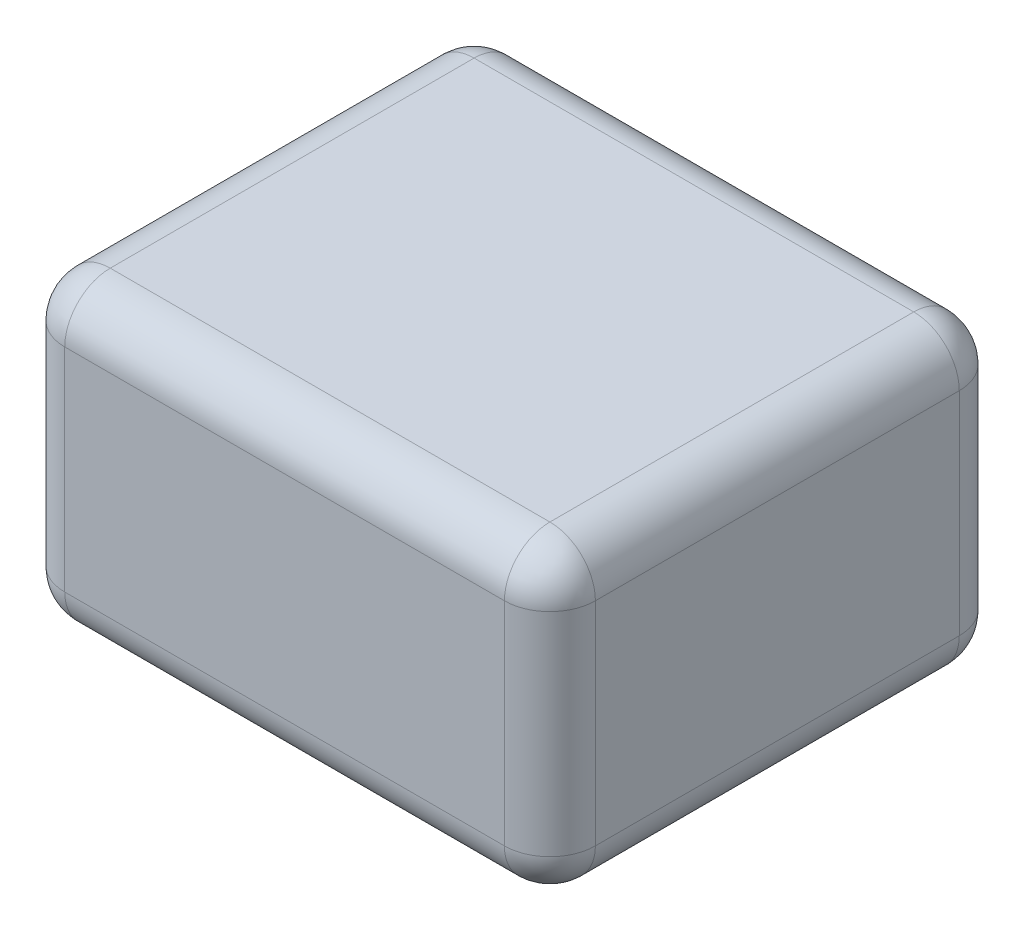
SolidWorks part; units mm, degrees
material "AISI 304"
ref_plane "Front Plane" through (0, 0, 0) normal (0, 0, 1) x (1, 0, 0)
ref_plane "Top Plane" through (0, 0, 0) normal (0, 1, 0) x (1, 0, 0)
ref_plane "Right Plane" through (0, 0, 0) normal (1, 0, 0) x (0, 0, -1)
sketch "Sketch1" plane through (0, 0, 0) normal (0, 0, 1) x (1, 0, 0)
  line L1 (-116.5919, -359.7775) -> (-81.5919, -359.7775)
  line L2 (-116.5919, -359.7775) -> (-116.5919, -379.7775)
  line L3 (-116.5919, -379.7775) -> (-81.5919, -379.7775)
  line L4 (-81.5919, -359.7775) -> (-81.5919, -379.7775)
extrude "Boss-Extrude1" add sketch "Sketch1" along normal blind 30
fillet "Fillet1" radius 3 12 edges at (-116.5919, -379.7775, 15) (-116.5919, -359.7775, 15) (-81.5919, -379.7775, 15) (-81.5919, -359.7775, 15) (-99.0919, -379.7775, 0) (-116.5919, -369.7775, 0) (-99.0919, -359.7775, 0) (-81.5919, -369.7775, 0) (-116.5919, -369.7775, 30) (-81.5919, -369.7775, 30) (-99.0919, -379.7775, 30) (-99.0919, -359.7775, 30)
